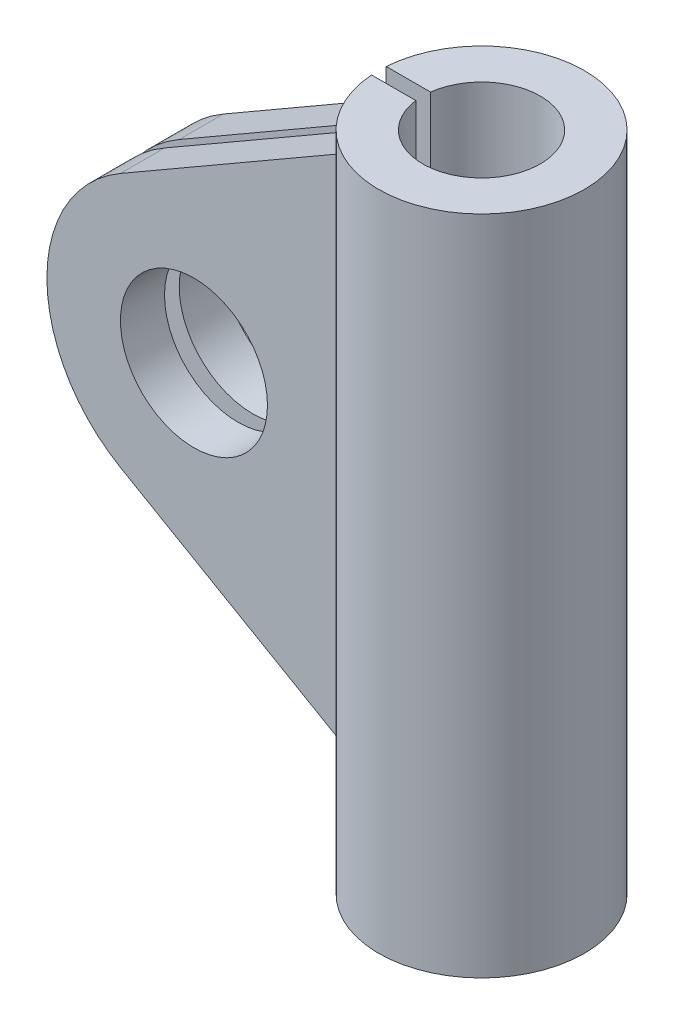
SolidWorks part; units mm, degrees
ref_plane "Спереди" through (0, 0, 0) normal (0, 0, 1) x (1, 0, 0)
ref_plane "Сверху" through (0, 0, 0) normal (0, 1, 0) x (1, 0, 0)
ref_plane "Справа" through (0, 0, 0) normal (1, 0, 0) x (0, 0, -1)
sketch "Эскиз1" plane through (0, 0, 0) normal (0, 0, 1) x (1, 0, 0)
  line L0 (-5, 8.6603) -> (10, 17.3205)
  line L1 (10, 17.3205) -> (10, -17.3205)
  line L2 (10, 0) -> (27.5935, 0) construction
  line L3 (-5, -8.6603) -> (10, -17.3205)
  circle A0 centre (0, 0) radius 10
  dimension "D1" = 20
  dimension "D2" = 60
extrude "Бобышка-Вытянуть1" add sketch "Эскиз1" along normal blind 7 contours A0 | A0 L3 L1 | A0 L1 L0
sketch "Эскиз2" plane through (0, 0, 0) normal (0, 1, 0) x (1, 0, 0)
  line L0 (10, -3.5) -> (28.2284, -3.5) construction
  line L1 (10, -7) -> (10, 0) construction
  circle A0 centre (16.0622, -3.5) radius 7
  point P6 (18.1724, -5)
  dimension "D1" = 14
extrude "Бобышка-Вытянуть2" add sketch "Эскиз2" along normal blind 20 and the other way blind 25
sketch "Эскиз3" plane through (0, 20, 0) normal (0, 1, 0) x (1, 0, 0)
  line L0 (16.0622, -3.5) -> (-10, -3.5) construction
  line L1 (-10, 0) -> (-10, -7) construction
  line L2 (-10, 0) -> (-10, -7) construction
  line L3 (16.0622, -3) -> (-10, -3)
  line L4 (16.0622, -3) -> (16.0622, -4)
  line L5 (16.0622, -4) -> (-10, -4)
  line L6 (-10, -3) -> (-10, -4)
  line L7 (16.0622, -3) -> (-10, -4) construction
  line L8 (16.0622, -4) -> (-10, -3) construction
  circle A0 centre (16.0622, -3.5) radius 4
  point P3 (-10, -3)
  point P7 (3.0311, -3.5)
  circle M2 centre (16.0622, -3.5) radius 7
  dimension "D1" = 8
  dimension "D2" = 1
extrude "Вырез-Вытянуть1" cut sketch "Эскиз3" against normal blind 55 contours L5 A0 L3 L4 | L3 A0 L5 L4 | L3 L6 L5 M2 | A0 L3 L5 M2
sketch "Эскиз4" plane through (0, 0, 7) normal (0, 0, 1) x (1, 0, 0)
  circle A0 centre (0, 0) radius 5
  dimension "D1" = 10
extrude "Вырез-Вытянуть2" cut sketch "Эскиз4" against normal blind 55
